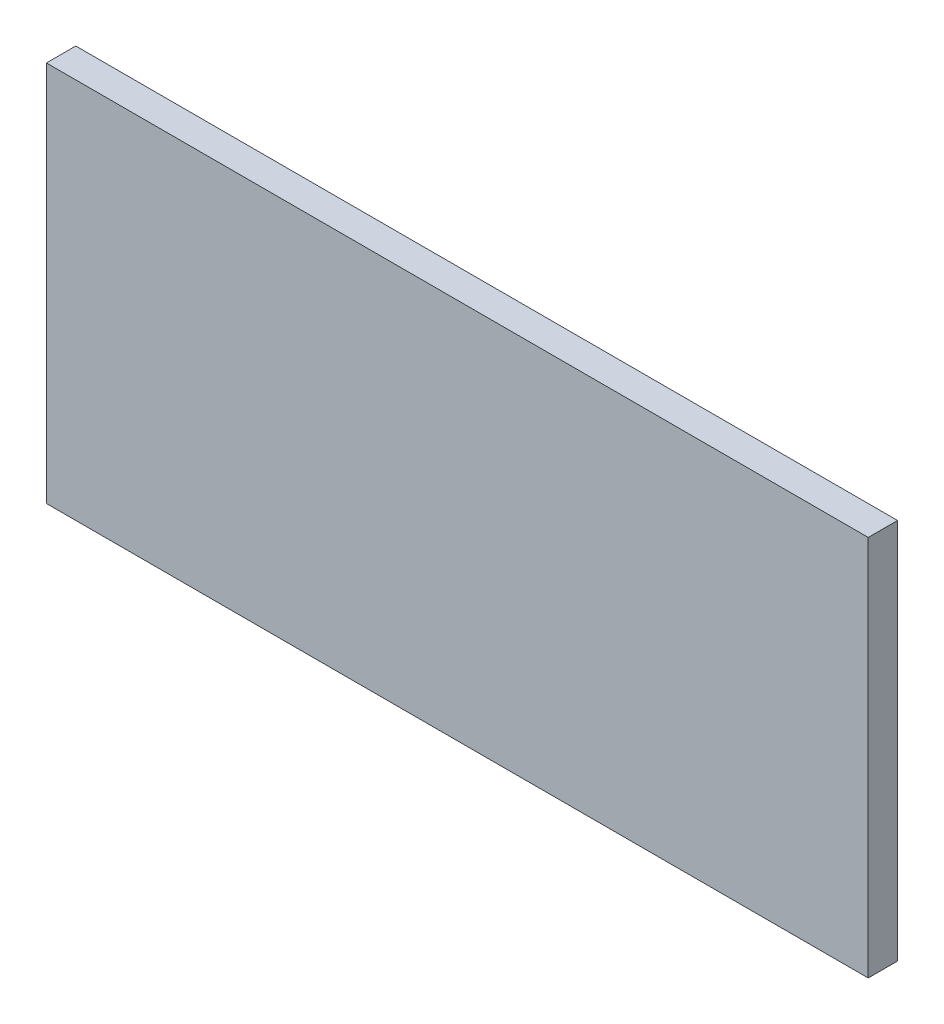
SolidWorks part; units mm, degrees
ref_plane "Спереди" through (0, 0, 0) normal (0, 0, 1) x (1, 0, 0)
ref_plane "Сверху" through (0, 0, 0) normal (0, 1, 0) x (1, 0, 0)
ref_plane "Справа" through (0, 0, 0) normal (1, 0, 0) x (0, 0, -1)
sketch "Skizze1" plane through (0, 0, 0) normal (0, 0, 1) x (1, 0, 0)
  line L1 (-14, 6) -> (14, 6)
  line L2 (-14, 6) -> (-14, -7)
  line L3 (-14, -7) -> (14, -7)
  line L4 (14, 6) -> (14, -7)
  dimension "D1" = 28
  dimension "D2" = 13
  dimension "D3" = 6
  dimension "D4" = 14
extrude "Aufsatz-Linear austragen1" add sketch "Skizze1" along normal blind 1
